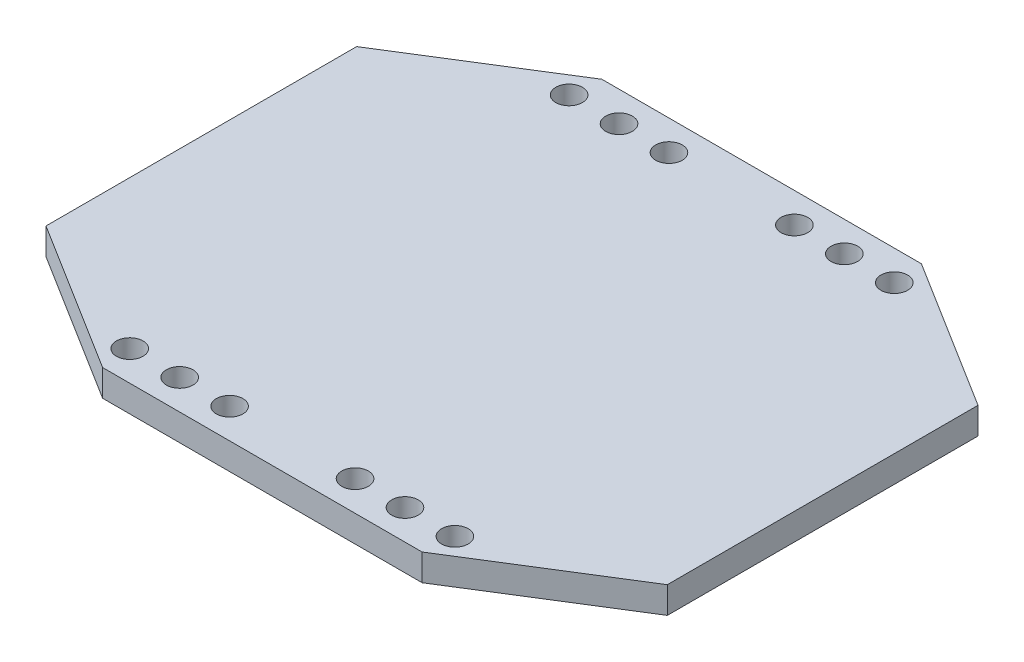
SolidWorks part; units mm, degrees
ref_plane "Front Plane" through (0, 0, 0) normal (0, 0, 1) x (1, 0, 0)
ref_plane "Top Plane" through (0, 0, 0) normal (0, 1, 0) x (1, 0, 0)
ref_plane "Right Plane" through (0, 0, 0) normal (1, 0, 0) x (0, 0, -1)
sketch "Sketch2" plane through (0, 0, 0) normal (0, 1, 0) x (1, 0, 0)
  line L0 (-28, -14) -> (-28, 14)
  line L1 (-28, 17.5) -> (28, 17.5) construction
  line L2 (-28, 17.5) -> (-28, -17.5) construction
  line L3 (-28, -17.5) -> (28, -17.5) construction
  line L4 (28, 17.5) -> (28, -17.5) construction
  line L5 (-28, 17.5) -> (28, -17.5) construction
  line L6 (-28, -17.5) -> (28, 17.5) construction
  line L7 (-28, 14) -> (-14.3972, 22.5)
  line L8 (28, 14) -> (14.3972, 22.5)
  line L9 (28, 14) -> (28, -14)
  line L10 (-14.3972, 22.5) -> (14.3972, 22.5)
  line L11 (-28, -14) -> (-14.3972, -22.5)
  line L12 (-14.3972, -22.5) -> (14.3972, -22.5)
  line L13 (14.3972, -22.5) -> (28, -14)
  circle A0 centre (-20, 9.5) radius 8 construction
  point P4 (0, 0)
  dimension "D3" = 16
  dimension "D1" = 56
  dimension "D2" = 35
  dimension "D4" = 8
  dimension "D5" = 8
  dimension "D6" = 3.5
  dimension "D7" = 3.5
  dimension "D8" = 58
  dimension "D9" = 5
  dimension "D10" = 58
extrude "Boss-Extrude1" add sketch "Sketch2" along normal mid plane 2.4
sketch "Sketch3" plane through (0, 1.2, 0) normal (0, 1, 0) x (1, 0, 0)
  line L0 (0, 0) -> (-26.4999, 42.3999) construction
  line L1 (0, 0) -> (-17.5, 0) construction
  line L2 (-17.5, 0) -> (-17.5, 28) construction
  line L3 (-33.2839, 38.1599) -> (-19.716, 46.6399) construction
  line L4 (-19.716, 46.6399) -> (-2.756, 19.504) construction
  line L5 (14.3972, 22.5) -> (-14.3972, 22.5) construction
  line L6 (-33.2839, 38.1599) -> (-16.324, 11.024) construction
  line L7 (-16.324, 11.024) -> (-2.756, 19.504) construction
  line L8 (-20.3715, 17.5) -> (-5.9623, 17.5) construction
  line L9 (-5.9623, 17.5) -> (-1.5035, 17.5) construction
  line L11 (-1.5035, 17.5) -> (-2.756, 19.504) construction
  line L12 (0, 0) -> (0, 22.5) construction
  line L13 (-14.6533, 19.8) -> (-5.6533, 19.8) construction
  circle A0 centre (-26.4999, 42.3999) radius 8 construction
  circle A1 centre (-14.6533, 19.8) radius 1.2
  circle A2 centre (-10.1533, 19.8) radius 1.2
  circle A3 centre (-5.6533, 19.8) radius 1.2
  dimension "D5" = 8
  dimension "D7" = 2.4
  dimension "D1" = 17.5
  dimension "D2" = 28
  dimension "D3" = 50
  dimension "D4" = 16
  dimension "D6" = 32
  dimension "D8" = 4.5
  dimension "D9" = 4.5
  dimension "D10" = 2.7
  dimension "D12" = 5
  dimension "D11" = 2.3
extrude "Cut-Extrude1" cut sketch "Sketch3" against normal through all
mirror "Mirror1" about plane through (0, 0, 0) normal (1, 0, 0) of "Cut-Extrude1"
mirror "Mirror2" about plane through (0, 0, 0) normal (0, 0, 1) of "Cut-Extrude1", "Mirror1"
equation "\"D7@Sketch2\"=\"D6@Sketch2\""
equation "\"D10@Sketch2\"=\"D8@Sketch2\""
equation "\"D9@Sketch3\"=\"D8@Sketch3\""
